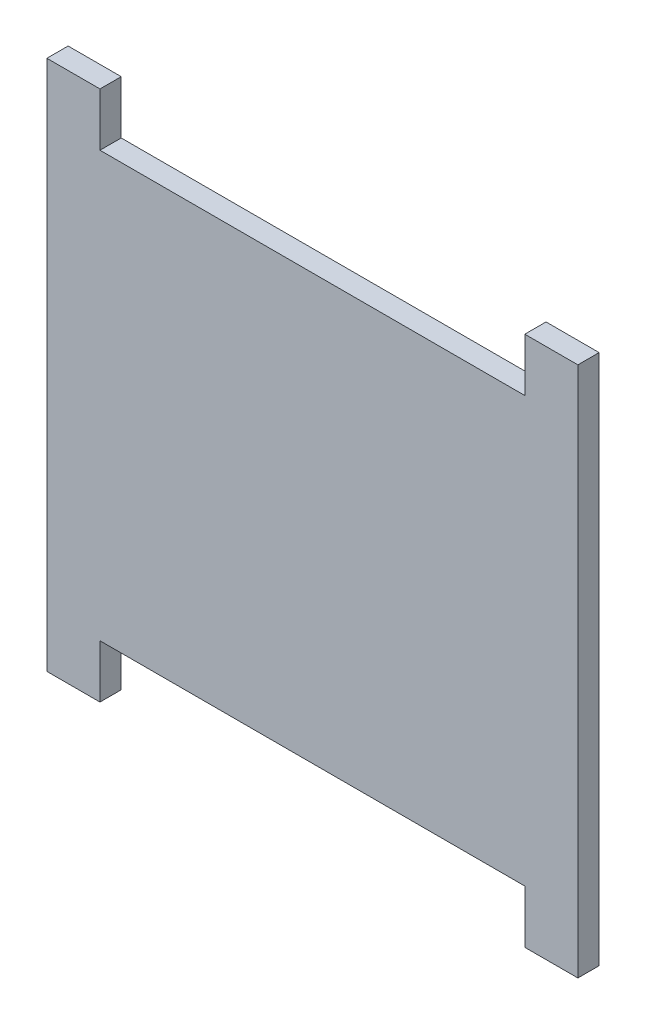
SolidWorks part; units mm, degrees
ref_plane "前视基准面" through (0, 0, 0) normal (0, 0, 1) x (1, 0, 0)
ref_plane "上视基准面" through (0, 0, 0) normal (0, 1, 0) x (1, 0, 0)
ref_plane "右视基准面" through (0, 0, 0) normal (1, 0, 0) x (0, 0, -1)
sketch "草图1" plane through (0, 0, 0) normal (0, 0, 1) x (1, 0, 0)
  line L0 (-20, 20) -> (50.5834, 20) construction
  line L1 (0, 0) -> (40, 0)
  line L2 (40, 0) -> (40, -5)
  line L3 (0, 40) -> (40, 40)
  line L4 (-5, 45) -> (-5, -5)
  line L5 (20, 40) -> (20, 0) construction
  line L6 (0, -5) -> (-5, -5)
  line L7 (40, 45) -> (45, 45)
  line L8 (40, 45) -> (40, 40)
  line L9 (40, -5) -> (45, -5)
  line L10 (45, 45) -> (45, -5)
  line L11 (0, 45) -> (0, 40)
  line L12 (0, 45) -> (-5, 45)
  line L13 (0, 0) -> (0, -5)
  dimension "D1" = 40
  dimension "D2" = 40
  dimension "D3" = 25
  dimension "D4" = 25
  dimension "D5" = 5
extrude "凸台-拉伸1" add sketch "草图1" along normal blind 2
